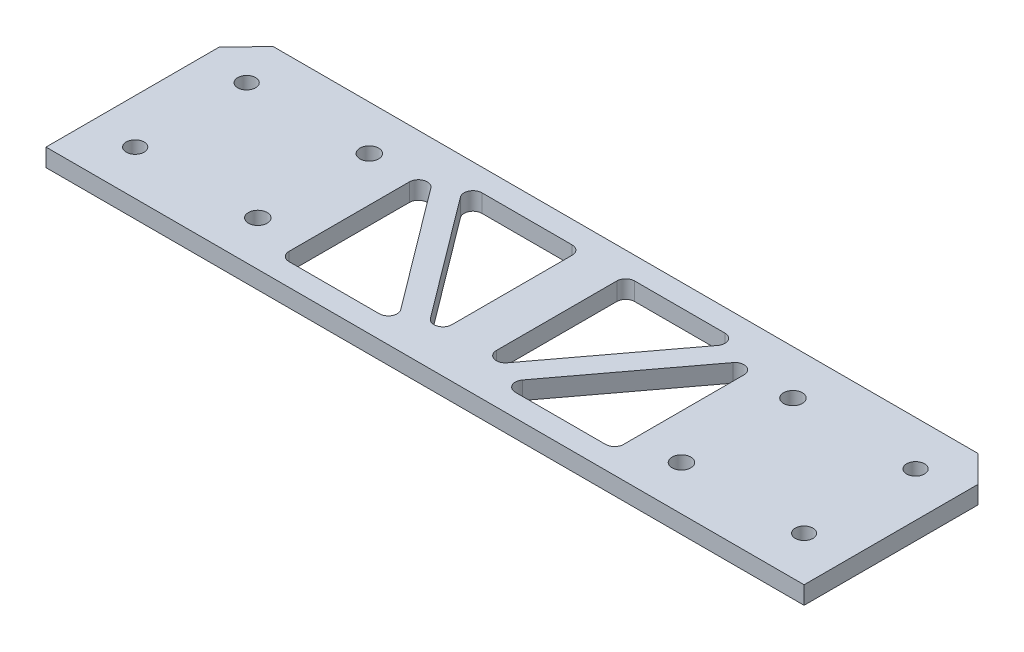
SolidWorks part; units mm, degrees
ref_plane "前视基准面" through (0, 0, 0) normal (0, 0, 1) x (1, 0, 0)
ref_plane "上视基准面" through (0, 0, 0) normal (0, 1, 0) x (1, 0, 0)
ref_plane "右视基准面" through (0, 0, 0) normal (1, 0, 0) x (0, 0, -1)
other "Configuration Table"
sketch "草图1" plane through (0, 0, 0) normal (0, 1, 0) x (1, 0, 0)
  line L0 (85, 45) -> (85, 0) construction
  line L1 (0, 0) -> (170, 0)
  line L2 (0, 0) -> (0, 45)
  line L3 (0, 45) -> (170, 45)
  line L4 (170, 0) -> (170, 45)
  line L5 (10, 35) -> (37.5, 35) construction
  circle A0 centre (10, 35) radius 2
  circle A1 centre (10, 10) radius 2
  circle A2 centre (160, 10) radius 2
  circle A3 centre (160, 35) radius 2
  circle A4 centre (37.5, 35) radius 2.1
  circle A5 centre (37.5, 10) radius 2.1
  circle A6 centre (132.5, 10) radius 2.1
  circle A7 centre (132.5, 35) radius 2.1
  dimension "D2" = 25
  dimension "D4" = 25
  dimension "D5" = 4.2
  dimension "D6" = 4
  dimension "D7" = 10
  dimension "D8" = 95
  dimension "D9" = 10
  dimension "D10" = 10
  dimension "D11" = 150
  dimension "D1" = 2
  dimension "D3" = 2
extrude "凸台-拉伸1" add sketch "草图1" along normal blind 4
sketch "草图4" plane through (0, 4, 0) normal (0, 1, 0) x (1, 0, 0)
  line L0 (0, 38.9095) -> (6, 45)
  line L2 (0, 45) -> (0, 38.9095)
  line L4 (6, 45) -> (0, 45)
  line L6 (170, 39) -> (164, 45)
  line L7 (164, 45) -> (170, 45)
  line L8 (170, 45) -> (170, 39)
  line L9 (0, 0) -> (0, 45) construction
  line L10 (-50.6654, 38.9095) -> (220.6654, 38.9095) construction
  dimension "D1" = 45
  dimension "D2" = 6
  dimension "D3" = 6
extrude "切除-拉伸1" cut sketch "草图4" against normal blind 4
sketch "草图5" plane through (0, 0, 0) normal (0, -1, 0) x (1, 0, 0)
  line L0 (47.5, -5) -> (47.5, -40)
  line L1 (47.5, -40) -> (73.75, -5)
  line L2 (73.75, -5) -> (47.5, -5)
  line L3 (53.75, -40) -> (80, -5)
  line L4 (80, -5) -> (80, -40)
  line L5 (80, -40) -> (53.75, -40)
  line L6 (90, -5) -> (90, -40)
  line L7 (90, -40) -> (116.25, -40)
  line L8 (116.25, -40) -> (90, -5)
  line L9 (96.25, -5) -> (122.5, -5)
  line L10 (122.5, -5) -> (122.5, -40)
  line L11 (122.5, -40) -> (96.25, -5)
  line L12 (85, -45) -> (85, 0) construction
  line L13 (6, -45) -> (164, -45) construction
  line L14 (0, 0) -> (170, 0) construction
  line L15 (170, 0) -> (170, -39) construction
  line L16 (0, 0) -> (0, -38.9095) construction
  dimension "D1" = 5
  dimension "D2" = 5
  dimension "D3" = 5
  dimension "D4" = 5
  dimension "D5" = 5
  dimension "D6" = 5
  dimension "D7" = 47.5
  dimension "D8" = 47.5
extrude "切除-拉伸2" cut sketch "草图5" against normal up to surface (4 mm away) up to face at (85, 4, -27.9849)
fillet "圆角1" radius 2 12 edges at (122.5, 2, -40) (96.25, 2, -5) (122.5, 2, -5) (116.25, 2, -40) (90, 2, -40) (90, 2, -5) (80, 2, -40) (53.75, 2, -40) (80, 2, -5) (73.75, 2, -5) (47.5, 2, -40) (47.5, 2, -5)
